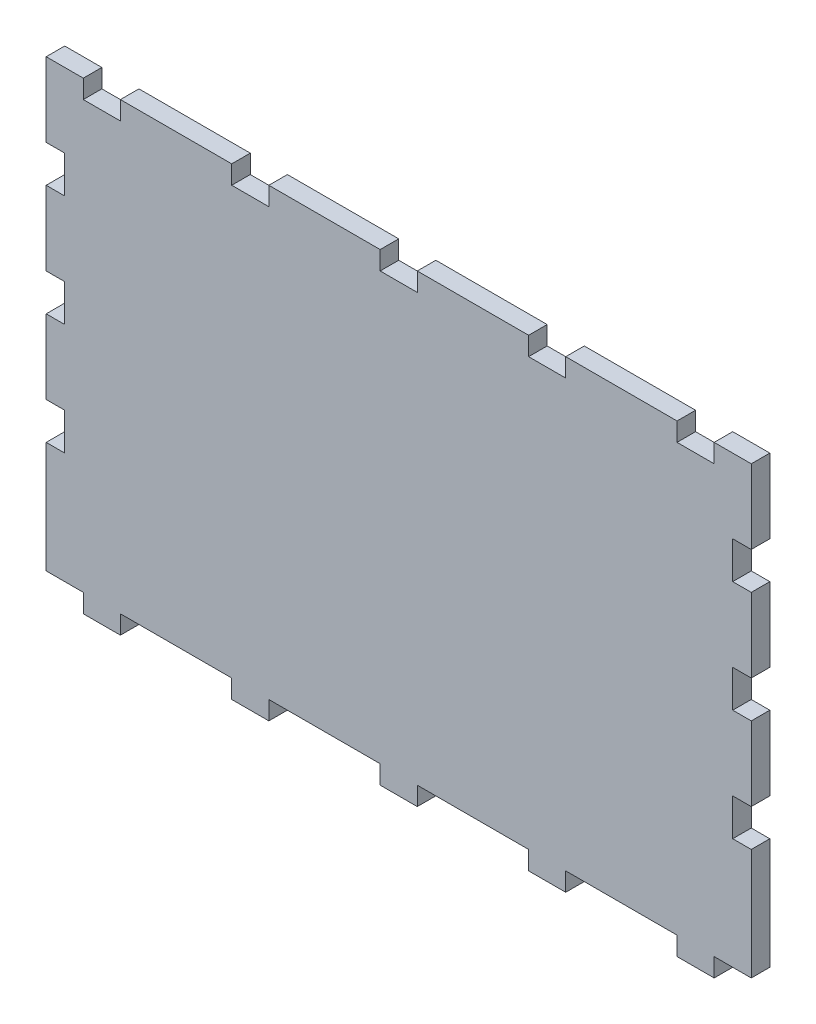
SolidWorks part; units mm, degrees
ref_plane "Ön Düzlem" through (0, 0, 0) normal (0, 0, 1) x (1, 0, 0)
ref_plane "Üst Düzlem" through (0, 0, 0) normal (0, 1, 0) x (1, 0, 0)
ref_plane "Sağ Düzlem" through (0, 0, 0) normal (1, 0, 0) x (0, 0, -1)
sketch "Sketch1" plane through (0, 0, 0) normal (0, 0, 1) x (1, 0, 0)
  line L0 (-85, 60) -> (-85, 55)
  line L1 (-95, -60) -> (-85, -60)
  line L2 (-95, -60) -> (-95, -30)
  line L3 (-95, 60) -> (-85, 60)
  line L4 (95, -60) -> (95, -30)
  line L5 (-95, -60) -> (95, 60) construction
  line L6 (-95, 60) -> (95, -60) construction
  line L7 (-85, 55) -> (-75, 55)
  line L8 (-75, 55) -> (-75, 60)
  line L9 (-45, 60) -> (-45, 55)
  line L10 (-35, 55) -> (-35, 60)
  line L11 (-45, 55) -> (-35, 55)
  line L12 (-5, 60) -> (-5, 55)
  line L13 (5, 55) -> (5, 60)
  line L14 (-5, 55) -> (5, 55)
  line L15 (35, 60) -> (35, 55)
  line L16 (45, 55) -> (45, 60)
  line L17 (35, 55) -> (45, 55)
  line L18 (75, 60) -> (75, 55)
  line L19 (85, 55) -> (85, 60)
  line L20 (75, 55) -> (85, 55)
  line L21 (-75, 60) -> (-45, 60)
  line L22 (-35, 60) -> (-5, 60)
  line L23 (5, 60) -> (35, 60)
  line L24 (45, 60) -> (75, 60)
  line L26 (-95, 0) -> (95, 0) construction
  line L27 (0, -53.6405) -> (0, 53.6405) construction
  line L28 (-95, 40) -> (-90, 40)
  line L29 (-90, 40) -> (-90, 30)
  line L30 (-90, 30) -> (-95, 30)
  line L31 (-90, 0) -> (-95, 0)
  line L32 (-95, 10) -> (-90, 10)
  line L33 (-90, 10) -> (-90, 0)
  line L34 (-90, -30) -> (-95, -30)
  line L35 (-95, -20) -> (-90, -20)
  line L36 (-90, -20) -> (-90, -30)
  line L37 (90, 30) -> (95, 30)
  line L38 (95, 40) -> (90, 40)
  line L39 (90, 40) -> (90, 30)
  line L40 (95, 10) -> (90, 10)
  line L41 (90, 10) -> (90, 0)
  line L42 (90, 0) -> (95, 0)
  line L43 (95, -20) -> (90, -20)
  line L44 (90, -20) -> (90, -30)
  line L45 (90, -30) -> (95, -30)
  line L46 (85, -65) -> (85, -60)
  line L47 (75, -65) -> (85, -65)
  line L48 (75, -60) -> (75, -65)
  line L49 (45, -65) -> (45, -60)
  line L50 (35, -65) -> (45, -65)
  line L51 (35, -60) -> (35, -65)
  line L52 (5, -65) -> (5, -60)
  line L53 (-5, -65) -> (5, -65)
  line L55 (-35, -65) -> (-35, -60)
  line L56 (-45, -65) -> (-35, -65)
  line L57 (-45, -60) -> (-45, -65)
  line L58 (-75, -65) -> (-75, -60)
  line L59 (-85, -65) -> (-75, -65)
  line L60 (-85, -60) -> (-85, -65)
  line L61 (-75, -60) -> (-45, -60)
  line L63 (5, -60) -> (35, -60)
  line L64 (45, -60) -> (75, -60)
  line L66 (-95, -20) -> (-95, 0)
  line L67 (-95, 10) -> (-95, 30)
  line L68 (-95, 40) -> (-95, 60)
  line L69 (95, 40) -> (95, 60)
  line L70 (95, 10) -> (95, 30)
  line L71 (95, -20) -> (95, 0)
  line L72 (-35, -60) -> (-5, -60)
  line L73 (-5, -65) -> (-5, -60)
  line L74 (85, -60) -> (95, -60)
  line L75 (95, 60) -> (85, 60)
  circle A1 centre (-30, 0) radius 45 construction
  point P0 (0, 0)
  dimension "D3" = 10
  dimension "D5" = 90
  dimension "D6" = 5
  dimension "D1" = 120
  dimension "D2" = 190
  dimension "D4" = 30
  dimension "D7" = 10
  dimension "D8" = 5
  dimension "D9" = 10
  dimension "D11" = 30
  dimension "D12" = 5
  dimension "D13" = 10
  dimension "D14" = 20
  dimension "D16" = 10
  dimension "D17" = 30
  dimension "D18" = 30
  dimension "D20" = 20
  dimension "D10" = 5
  dimension "D15" = 3
extrude "Boss-Extrude1" add sketch "Sketch1" along normal blind 5
